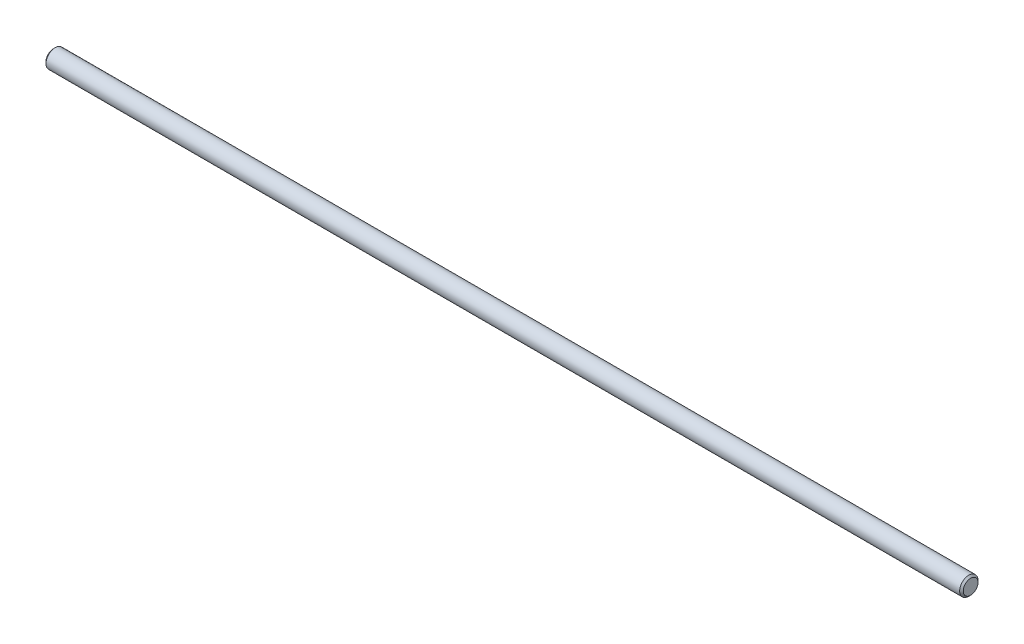
SolidWorks part; units mm, degrees
material "SUS304相当"
ref_plane "Front Plane" through (0, 0, 0) normal (0, 0, 1) x (1, 0, 0)
ref_plane "Top Plane" through (0, 0, 0) normal (0, 1, 0) x (1, 0, 0)
ref_plane "Right Plane" through (0, 0, 0) normal (1, 0, 0) x (0, 0, -1)
sketch "Sketch1" plane through (0, 0, 0) normal (0, 0, 1) x (1, 0, 0)
  line L0 (0, 0) -> (250, 0) construction
  line L1 (0, 0) -> (0, 2.01)
  line L2 (0, 2.01) -> (0.49, 2.5)
  line L3 (0.49, 2.5) -> (249.51, 2.5)
  line L4 (249.51, 2.5) -> (250, 2.01)
  line L5 (250, 2.01) -> (250, 0)
  line L6 (0, 0) -> (250, 0)
  dimension "L" = 250
  dimension "MSM_1" = 0.49
  dimension "FIX_1" = 45
  dimension "M" = 5
revolve "Revolve1" add sketch "Sketch1" angle 360 about L0
cosmetic thread "Thread1"
cosmetic thread "Thread2" [suppressed]
sketch "Sketch2" [suppressed] plane through (0, 0, 0) normal (0, 0, 1) x (1, 0, 0)
  line L1 (0, 0.5) -> (1, 0.5)
  line L2 (0, 0.5) -> (0, -0.5)
  line L3 (0, -0.5) -> (1, -0.5)
  line L4 (1, 0.5) -> (1, -0.5)
  dimension "W_1" = 1
extrude "Cut-Extrude1" [suppressed] cut sketch "Sketch2" against normal through all and the other way through all
ref_plane "Plane1" [suppressed] through (4, 0, 0) normal (1, 0, 0) x (0, 0, -1)
sketch "Sketch4" [suppressed] plane through (4, 0, 0) normal (1, 0, 0) x (0, 0, -1)
  line L1 (1.5, 1.3229) -> (1.5, -1.3229)
  line L2 (-1.5, 1.3229) -> (-1.5, -1.3229)
  arc A0 (-1.5, 1.3229) -> (-1.5, -1.3229) centre (0, 0) ccw
  arc A1 (1.5, -1.3229) -> (1.5, 1.3229) centre (0, 0) ccw
  dimension "S" = 3
extrude "Cut-Extrude2" [suppressed] cut sketch "Sketch4" along normal blind 3.5
equation "\"Factor\"= 1.082532"
equation "\"Pitch_M\"= IIF ( \"M\" = 30 , 3.5 , IIF ( \"M\" = 24 , 3 , IIF ( \"M\" = 22 , 2.5 , IIF ( \"M\" = 20 , 2.5 , IIF ( \"M\" = 18 , 2.5 , IIF ( \"M\" = 16 , 2 , IIF ( \"M\" = 14 , 2 , IIF ( \"M\" = 12 , 1.75 , IIF ( \"M\" = 10 , 1.5 , IIF ( \"M\" = 8 , 1.25 , IIF ( \"M\" = 6 , 1 , IIF ( \"M\" = 5 , 0.8 , IIF ( \"M\" = 4 , 0.7 , IIF ( \"M\" = 3 , 0.5 , IIF ( \"M\" = 2.6 , 0.45 , IIF ( \"M\" = 2.5 , 0.45 , 0.4 ) ) ) ) ) ) ) ) ) ) ) ) ) ) ) )"
equation "\"ATD_1\"= round ( \"M\" - \"Factor\" * \"Pitch_M\" , 3 )"
equation "\"Pitch_M1\"= IIF ( \"M\" = 30 , 1.5 , IIF ( \"M\" = 25 , 1.5 , IIF ( \"M\" = 20 , 1.5 , IIF ( \"M\" = 16 , 1.5 , IIF ( \"M\" = 15 , 1 , IIF ( \"M\" = 12 , 1.25 , IIF ( \"M\" = 10 , 1.25 , IIF ( \"M\" = 8 , 1 , IIF ( \"M\" = 6 , 0.75 , IIF ( \"M\" = 5 , 0.5 , IIF ( \"M\" = 4 , 0.5 , 0.35 ) ) ) ) ) ) ) ) ) ) )"
equation "\"ATD_2\"= round ( \"M\" - \"Factor\" * \"Pitch_M1\" , 3 )"
